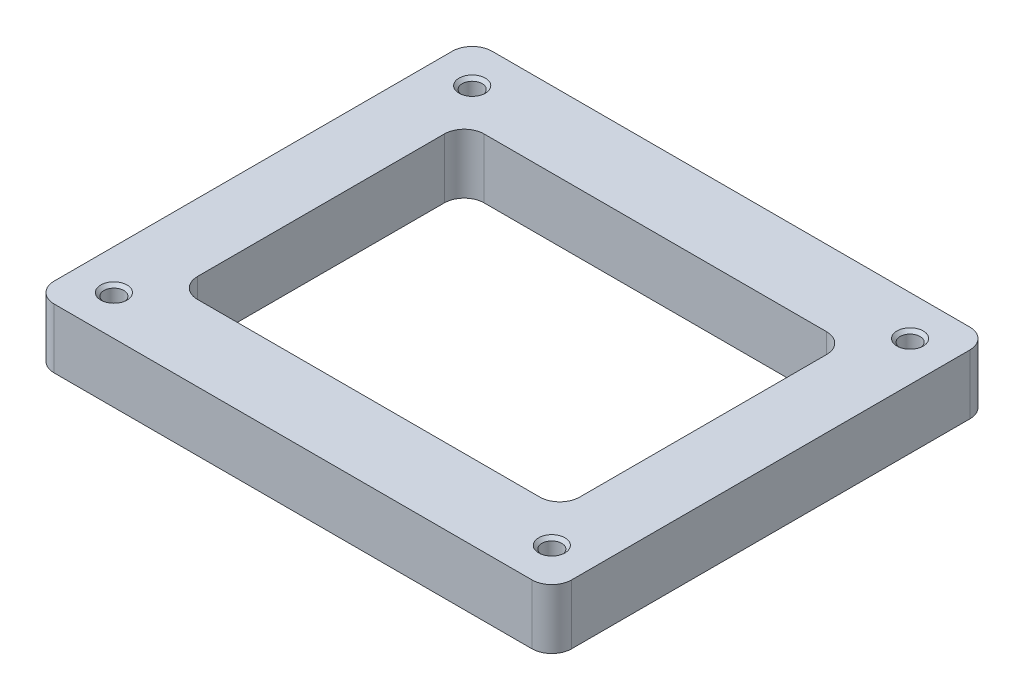
SolidWorks part; units mm, degrees
material "Custom Plastic"
ref_plane "Front Plane" through (0, 0, 0) normal (0, 0, 1) x (1, 0, 0)
ref_plane "Top Plane" through (0, 0, 0) normal (0, 1, 0) x (1, 0, 0)
ref_plane "Right Plane" through (0, 0, 0) normal (1, 0, 0) x (0, 0, -1)
sketch "Sketch1" plane through (0, 0, 0) normal (0, 1, 0) x (1, 0, 0)
  line L1 (-47.7196, 50.488) -> (34.8304, 50.488)
  line L2 (-47.7196, 50.488) -> (-47.7196, -19.362)
  line L3 (-47.7196, -19.362) -> (34.8304, -19.362)
  line L4 (34.8304, 50.488) -> (34.8304, -19.362)
  dimension "D1" = 82.55
  dimension "D2" = 69.85
extrude "Boss-Extrude1" add sketch "Sketch1" along normal blind 9.525
sketch "Sketch2" plane through (0, 9.525, 0) normal (0, 1, 0) x (1, 0, 0)
  line L0 (-6.4446, 50.488) -> (-6.4446, -19.362)
  line L5 (34.8304, 50.488) -> (-47.7196, 50.488) construction
  line L6 (-47.7196, -19.362) -> (34.8304, -19.362) construction
  line L7 (-47.7196, 15.563) -> (34.8304, 15.563)
  line L8 (-47.7196, 50.488) -> (-47.7196, -19.362) construction
  line L9 (34.8304, -19.362) -> (34.8304, 50.488) construction
  line L10 (-36.9246, 38.423) -> (24.0354, 38.423)
  line L11 (-36.9246, 38.423) -> (-36.9246, -7.297)
  line L12 (-36.9246, -7.297) -> (24.0354, -7.297)
  line L13 (24.0354, -7.297) -> (24.0354, 38.423)
  point P16 (-6.4446, 15.563)
  dimension "D1" = 60.96
  dimension "D2" = 82.55
  dimension "D3" = 10.795
  dimension "D4" = 10.795
  dimension "D5" = 45.72
  dimension "D6" = 12.065
extrude "Cut-Extrude1" cut sketch "Sketch2" against normal through all contours L10 L11 L7 L0 | L7 L13 L10 L0 | L12 L13 L7 L0 | L11 L12 L0 L7
sketch "Sketch5" plane through (0, 9.525, 0) normal (0, 1, 0) x (1, 0, 0)
  line L0 (-47.7196, 50.488) -> (-47.7196, -19.362) construction
  line L2 (34.8304, 50.488) -> (-47.7196, 50.488) construction
  line L3 (34.8304, -19.362) -> (34.8304, 50.488) construction
  line L4 (-47.7196, -19.362) -> (34.8304, -19.362) construction
  circle A0 centre (-41.3696, 44.138) radius 1.5875
  circle A1 centre (28.4804, 44.138) radius 1.5875
  circle A2 centre (28.4804, -13.012) radius 1.5875
  circle A3 centre (-41.3696, -13.012) radius 1.5875
  dimension "D1" = 3.175
  dimension "D2" = 3.175
  dimension "D3" = 3.175
  dimension "D4" = 3.175
  dimension "D5" = 6.35
  dimension "D6" = 6.35
  dimension "D7" = 6.35
  dimension "D8" = 6.35
  dimension "D9" = 6.35
  dimension "D10" = 6.35
  dimension "D11" = 6.35
  dimension "D12" = 6.35
extrude "Cut-Extrude2" cut sketch "Sketch5" against normal through all
fillet "Fillet1" radius 3.175 8 edges at (-47.7196, 4.7625, -50.488) (34.8304, 4.7625, -50.488) (34.8304, 4.7625, 19.362) (-47.7196, 4.7625, 19.362) (-36.9246, 4.7625, -38.423) (24.0354, 4.7625, -38.423) (24.0354, 4.7625, 7.297) (-36.9246, 4.7625, 7.297)
chamfer "Chamfer1" distance 0.508 angle 45 4 edges at (28.4804, 9.525, -42.5505) (28.4804, 9.525, 14.5995) (-41.3696, 9.525, -42.5505) (-41.3696, 9.525, 14.5995)
